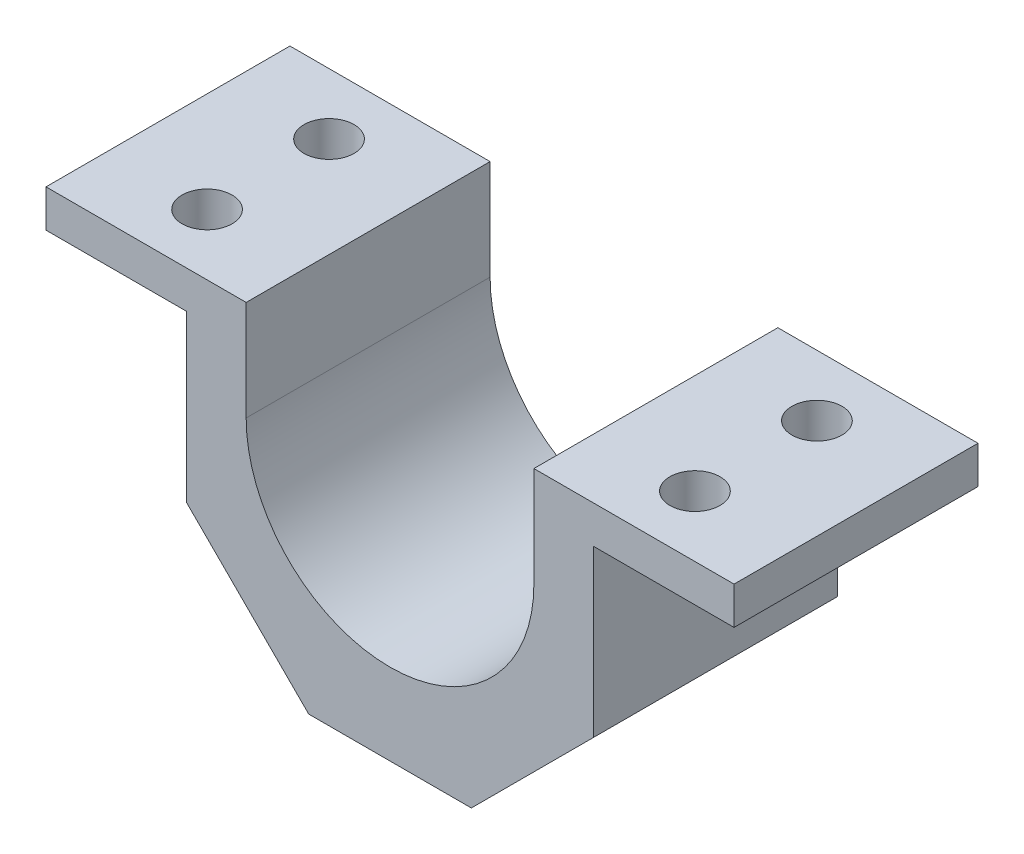
SolidWorks part; units mm, degrees
ref_plane "Front Plane" through (0, 0, 0) normal (0, 0, 1) x (1, 0, 0)
ref_plane "Top Plane" through (0, 0, 0) normal (0, 1, 0) x (1, 0, 0)
ref_plane "Right Plane" through (0, 0, 0) normal (1, 0, 0) x (0, 0, -1)
sketch "Sketch1" plane through (0, 0, 0) normal (0, 0, 1) x (1, 0, 0)
  line L0 (-55, 16) -> (-55, 10)
  line L1 (-55, 10) -> (-32.5, 10)
  line L2 (-32.5, 10) -> (-32.5, -16.5)
  line L3 (-32.5, -16.5) -> (-13, -36)
  line L4 (-13, -36) -> (13, -36)
  line L5 (-55, 16) -> (-23, 16)
  line L6 (-23, 16) -> (-23, 0)
  line L7 (0, 33.1875) -> (0, 12) construction
  line L8 (0, -36) -> (-66.375, -36) construction
  line L9 (23, 16) -> (23, 0)
  line L10 (55, 16) -> (23, 16)
  line L11 (32.5, -16.5) -> (13, -36)
  line L12 (32.5, 10) -> (32.5, -16.5)
  line L13 (55, 10) -> (32.5, 10)
  line L14 (55, 16) -> (55, 10)
  arc A0 (-23, 0) -> (23, 0) centre (0, 0) ccw
  point P14 (0, 0)
  point P19 (0, -36)
  dimension "D5" = 23
  dimension "D1" = 6
  dimension "D2" = 16
  dimension "D3" = 32.5
  dimension "D4" = 13
  dimension "D6" = 45
  dimension "D7" = 55
  dimension "D8" = 52
extrude "Boss-Extrude1" add sketch "Sketch1" along normal blind 39
sketch "Sketch2" plane through (0, 16, 0) normal (0, 1, 0) x (1, 0, 0)
  line L0 (-70.863, -19.5) -> (-35.2682, -19.5) construction
  line L2 (-23, 0) -> (-55, 0) construction
  line L3 (0, 11.3053) -> (0, -54.8771) construction
  line L4 (-55, -39) -> (-55, 0) construction
  circle A0 centre (-39, -9.75) radius 4
  circle A1 centre (39, -9.75) radius 4
  circle A2 centre (39, -29.25) radius 4
  circle A3 centre (-39, -29.25) radius 4
  point P9 (-40.0577, -9.7033)
  dimension "D2" = 8
  dimension "D1" = 19.5
  dimension "D3" = 9.75
  dimension "D4" = 16
extrude "Cut-Extrude1" cut sketch "Sketch2" against normal blind 39 contours A0 | A3 | A1 | A2
